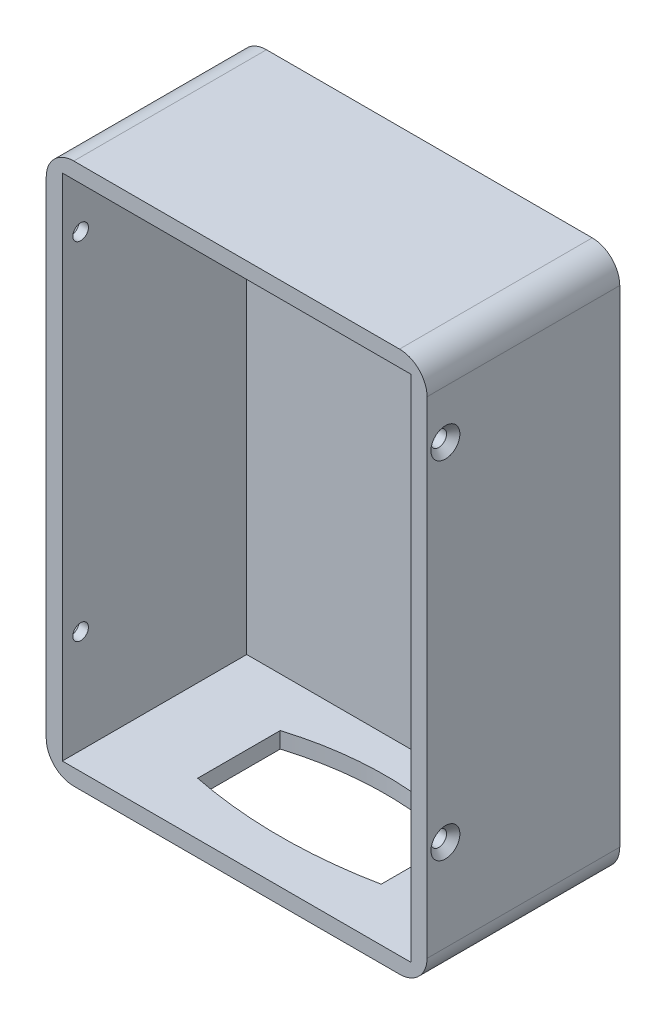
SolidWorks part; units mm, degrees
ref_plane "Přední rovina" through (0, 0, 0) normal (0, 0, 1) x (1, 0, 0)
ref_plane "Horní rovina" through (0, 0, 0) normal (0, 1, 0) x (1, 0, 0)
ref_plane "Pravá rovina" through (0, 0, 0) normal (1, 0, 0) x (0, 0, -1)
sketch "Skica1" plane through (0, 0, 0) normal (0, 0, 1) x (1, 0, 0)
  line L0 (-41.5, 53) -> (-41.5, -53)
  line L1 (-38, 55.5) -> (38, 55.5)
  line L2 (-38, 55.5) -> (-38, -55.5)
  line L3 (-38, -55.5) -> (38, -55.5)
  line L4 (38, 55.5) -> (38, -55.5)
  line L5 (-38, 55.5) -> (38, -55.5) construction
  line L6 (-38, -55.5) -> (38, 55.5) construction
  line L7 (-35.5, -59) -> (35.5, -59)
  line L8 (41.5, 53) -> (41.5, -53)
  line L9 (-35.5, 59) -> (35.5, 59)
  line L10 (-41.5, 59) -> (-41.5, -59) construction
  line L11 (-41.5, -59) -> (41.5, -59) construction
  line L12 (41.5, 59) -> (41.5, -59) construction
  line L13 (-41.5, 59) -> (41.5, 59) construction
  arc A0 (-41.5, -53) -> (-35.5, -59) centre (-35.5, -53) ccw
  arc A1 (35.5, -59) -> (41.5, -53) centre (35.5, -53) ccw
  arc A2 (41.5, 53) -> (35.5, 59) centre (35.5, 53) ccw
  arc A3 (-41.5, 53) -> (-35.5, 59) centre (-35.5, 53) cw
  point P0 (0, 0)
  dimension "D4" = 6
  dimension "D1" = 76
  dimension "D2" = 111
  dimension "D3" = 3.5
extrude "Přidat vysunutím1" add sketch "Skica1" along normal blind 42
sketch "Skica2" plane through (0, 0, 0) normal (0, 0, -1) x (-1, 0, 0)
  line L1 (38, 55.5) -> (-38, 55.5)
  line L2 (38, 55.5) -> (38, -55.5)
  line L3 (38, -55.5) -> (-38, -55.5)
  line L4 (-38, 55.5) -> (-38, -55.5)
  line L5 (38, 55.5) -> (-38, -55.5) construction
  line L6 (38, -55.5) -> (-38, 55.5) construction
  point P0 (0, 0)
extrude "Přidat vysunutím2" add sketch "Skica2" against normal blind 1.8
sketch "Skica3" plane through (0, -59, 0) normal (0, -1, 0) x (1, 0, 0)
  line L0 (0, 0) -> (0, 9.5)
  line L1 (0, 9.5) -> (20, 9.5)
  line L2 (20, 9.5) -> (20, 32.5)
  line L3 (20, 32.5) -> (-20, 32.5)
  line L4 (-20, 32.5) -> (-20, 9.5)
  line L5 (-20, 9.5) -> (0, 9.5)
  line L6 (0, 9.5) -> (0, 32.5)
  arc A0 (-20, 30.5) -> (20, 30.5) centre (0, -68.5) cw
  arc A1 (-20, 12.5) -> (20, 12.5) centre (0, 77.6667) ccw
  point P3 (-20, 12.5)
  point P8 (20, 12.5)
  point P9 (20, 30.5)
  point P10 (-20, 30.5)
  dimension "D1" = 9.5
  dimension "D2" = 20
  dimension "D3" = 23
  dimension "D4" = 3
  dimension "D5" = 3
  dimension "D6" = 2
  dimension "D7" = 2
extrude "Odebrat vysunutím1" cut sketch "Skica3" against normal up to next contours L4 A1 L6 A0 | L6 A1 L2 A0
sketch "Skica4" plane through (41.5, 0, 0) normal (1, 0, 0) x (0, 0, -1)
  line L0 (-38, 53) -> (-38, -53)
  line L1 (-42, 53) -> (0, 53) construction
  line L2 (-42, -53) -> (0, -53) construction
  line L3 (-38, 0) -> (0, 0)
  line L4 (0, -53) -> (0, 53) construction
  point P6 (-38, -33.09)
  point P7 (-38, 42.4)
  dimension "D1" = 4
  dimension "D2" = 42.4
  dimension "D3" = 33.09
hole_wizard "Kuželové zahloubení pro M3 šroubu se zápustnou hlavou plochou1" positions "Skica5" profile "Skica6" countersink size "M3" standard "DIN"
sketch "Skica5" plane through (41.5, 0, 0) normal (1, 0, 0) x (0, 0, -1)
  point P0 (-38, -33.09)
  point P3 (-38, 42.4)
sketch "Skica6" plane through (41.5, -33.09, 38) normal (0, 1, 0) x (0, 0, -1)
  line L0 (0, 0) -> (0, 83)
  line L1 (0, 83) -> (1.7, 83)
  line L2 (1.7, 83) -> (1.7, 1.45)
  line L3 (1.7, 1.45) -> (3.15, 0)
  line L5 (3.15, 0) -> (0, 0)
  line L6 (-1.7, 1.45) -> (-3.15, 0) construction
  line L11 (0, -6.35) -> (0, 107.95) construction
  dimension "Průměr díry skrz" = 3.4
  dimension "Hloubka díry skrz" = 83
  dimension "Průměr blíz. kuž. zahloubení" = 6.3
  dimension "Úhel blíz. kuž. zahloubení" = 90
ref_plane "Rovina1" through (0, 0, 0) normal (1, 0, 0) x (0, 0, -1)
mirror "Zrcadlit1" about plane through (0, 0, 0) normal (1, 0, 0) of "Kuželové zahloubení pro M3 šroubu se zápustnou hlavou plochou1"
